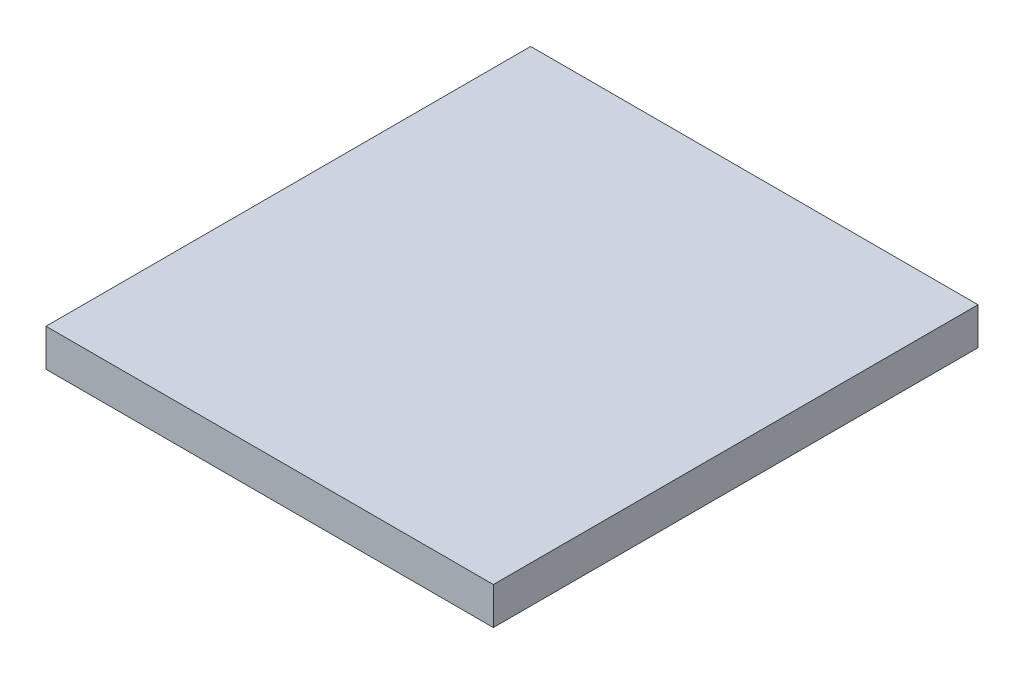
SolidWorks part; units mm, degrees
ref_plane "Front Plane" through (0, 0, 0) normal (0, 0, 1) x (1, 0, 0)
ref_plane "Top Plane" through (0, 0, 0) normal (0, 1, 0) x (1, 0, 0)
ref_plane "Right Plane" through (0, 0, 0) normal (1, 0, 0) x (0, 0, -1)
other "Configuration Table"
sketch "Sketch1" plane through (0, 0, 0) normal (0, 0, 1) x (1, 0, 0)
  line L1 (-30, 30) -> (30, 30)
  line L2 (-30, 30) -> (-30, 35)
  line L3 (-30, 35) -> (30, 35)
  line L4 (30, 30) -> (30, 35)
extrude "KAP_agiz_kapagi_PC_1" add sketch "Sketch1" against normal blind 65 from offset 25 separate body
